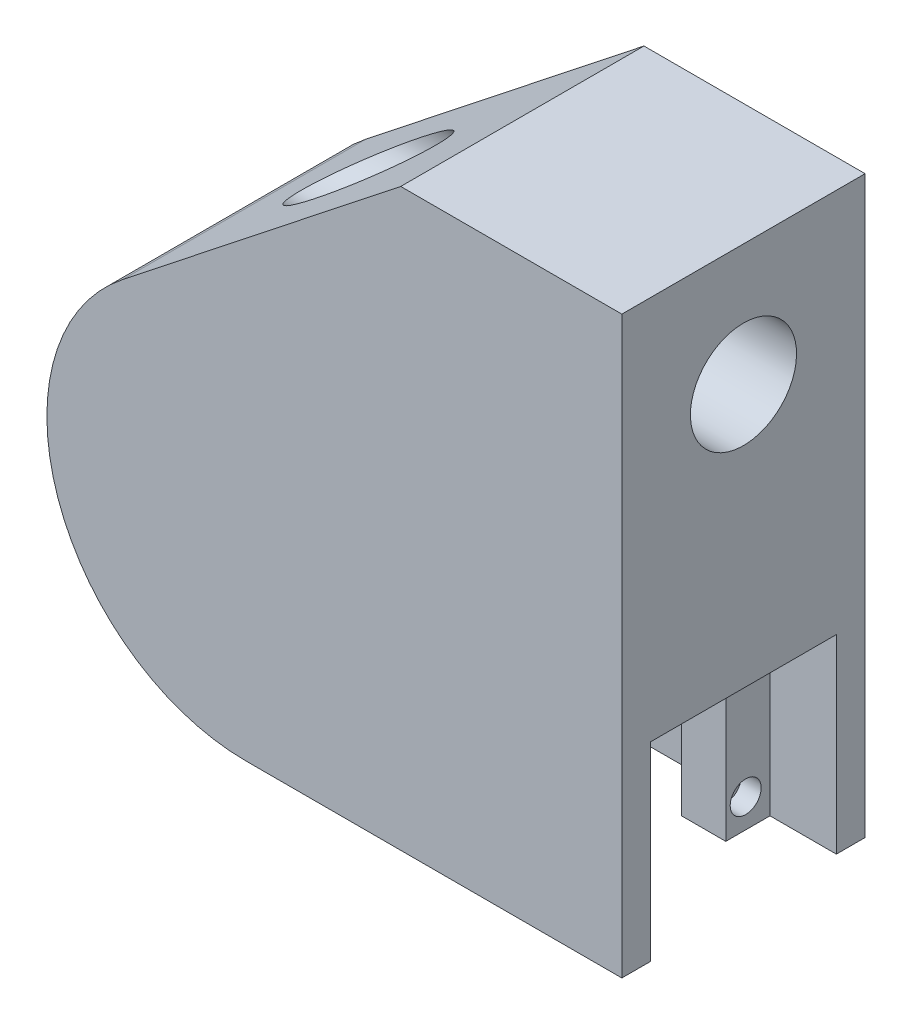
SolidWorks part; units mm, degrees
ref_plane "Ebene vorne" through (0, 0, 0) normal (0, 0, 1) x (1, 0, 0)
ref_plane "Ebene oben" through (0, 0, 0) normal (0, 1, 0) x (1, 0, 0)
ref_plane "Ebene rechts" through (0, 0, 0) normal (1, 0, 0) x (0, 0, -1)
sketch "Skizze1" plane through (0, 0, 0) normal (0, 0, 1) x (1, 0, 0)
  line L0 (35, 85) -> (-27.8961, 35.3102)
  line L1 (85, 85) -> (35, 85)
  line L2 (85, 85) -> (85, 35)
  line L3 (85, 35) -> (35, 35)
  line L4 (35, 85) -> (35, 35)
  line L5 (85, 85) -> (35, 35) construction
  line L6 (85, 35) -> (35, 85) construction
  line L7 (85, 35) -> (85, -45)
  line L8 (85, -45) -> (0, -45)
  circle A0 centre (0, 0) radius 45
  point P3 (60, 60)
  point P9 (0, 0)
  point P12 (-28.951, 34.4505)
  dimension "D1" = 90
  dimension "D2" = 50
  dimension "D3" = 50
  dimension "D4" = 60
  dimension "D5" = 60
extrude "Aufsatz-Linear austragen2" add sketch "Skizze1" along normal blind 55 contours A0 L8 L7 L3 L4 L0 | L1 L4 L3 L2 | A0
sketch "Skizze3" plane through (0, -45, 0) normal (0, -1, 0) x (1, 0, 0)
  line L0 (19, 55) -> (19, 0)
  line L1 (70, 55) -> (19, 55)
  line L2 (70, 55) -> (70, 48.5)
  line L3 (70, 48.5) -> (19, 48.5)
  line L4 (19, 55) -> (19, 48.5)
  line L5 (70, 55) -> (19, 48.5) construction
  line L6 (70, 48.5) -> (19, 55) construction
  line L7 (85, 48.5) -> (85, 6.5)
  line L8 (70, 48.5) -> (60, 48.5)
  line L9 (70, 48.5) -> (70, 38.5)
  line L10 (70, 38.5) -> (60, 38.5)
  line L11 (60, 48.5) -> (60, 38.5)
  line L12 (70, 48.5) -> (60, 38.5) construction
  line L13 (70, 38.5) -> (60, 48.5) construction
  line L14 (70, 0) -> (19, 0)
  line L15 (70, 0) -> (70, 6.5)
  line L16 (70, 6.5) -> (19, 6.5)
  line L17 (19, 0) -> (19, 6.5)
  line L18 (70, 0) -> (19, 6.5) construction
  line L19 (70, 6.5) -> (19, 0) construction
  line L20 (70, 6.5) -> (60, 6.5)
  line L21 (70, 6.5) -> (70, 16.5)
  line L22 (70, 16.5) -> (60, 16.5)
  line L23 (60, 6.5) -> (60, 16.5)
  line L24 (70, 6.5) -> (60, 16.5) construction
  line L25 (70, 16.5) -> (60, 6.5) construction
  line L26 (85, 55) -> (85, 0) construction
  line L28 (70, 55) -> (85, 55)
  line L29 (70, 55) -> (70, 48.5)
  line L30 (70, 48.5) -> (85, 48.5)
  line L31 (85, 55) -> (85, 48.5)
  line L32 (70, 55) -> (85, 48.5) construction
  line L33 (70, 48.5) -> (85, 55) construction
  line L34 (70, 0) -> (85, 0)
  line L35 (70, 0) -> (70, 6.5)
  line L36 (70, 6.5) -> (85, 6.5)
  line L37 (85, 0) -> (85, 6.5)
  line L38 (70, 0) -> (85, 6.5) construction
  line L39 (70, 6.5) -> (85, 0) construction
  point P4 (44.5, 51.75)
  point P11 (65, 43.5)
  point P16 (44.5, 3.25)
  point P21 (65, 11.5)
  point P25 (77.5, 51.75)
  point P27 (77.5, 3.25)
  point P28 (0, 0)
  line M7 (85, 0) -> (85, 55)
  dimension "D1" = 42
  dimension "D2" = 6.5
  dimension "D3" = 22
  dimension "D4" = 10
  dimension "D5" = 10
  dimension "D6" = 41
  dimension "D7" = 15
extrude "Schnitt-Linear austragen1" cut sketch "Skizze3" against normal blind 43 contours L16 L23 L22 L10 L11 L3 L0 M7
sketch "Skizze4" plane through (70, 0, 0) normal (1, 0, 0) x (0, 0, -1)
  line L0 (-38.5, -2) -> (-48.5, -2) construction
  line L3 (-48.5, -2) -> (-6.5, -2)
  line L4 (-48.5, -2) -> (-48.5, -44)
  line L5 (-48.5, -44) -> (-6.5, -44)
  line L6 (-6.5, -2) -> (-6.5, -44)
  line L7 (-48.5, -2) -> (-44.0604, -6.4396) construction
  line L8 (-48.5, -44) -> (-6.5, -2) construction
  line L9 (-55, -45) -> (-48.5, -45) construction
  line L10 (-41.9391, -8.5609) -> (-6.5, -44) construction
  arc A0 (-44.0235, -8.5965) -> (-13.0965, -39.5235) centre (-27.5, -23) ccw
  circle A1 centre (-12.0002, -7.5002) radius 1.5
  circle A2 centre (-12.0002, -38.4998) radius 1.5
  circle A3 centre (-42.9998, -38.4998) radius 1.5
  circle A4 centre (-42.9998, -7.5002) radius 1.5
  arc A5 (-13.0965, -6.4765) -> (-41.9035, -6.4765) centre (-27.5, -23) ccw
  arc A6 (-10.9765, -37.4035) -> (-10.9765, -8.5965) centre (-27.5, -23) ccw
  point P8 (-27.5, -23)
  point P23 (-27.5, -23)
  dimension "D4" = 4
  dimension "D5" = 3
  dimension "D1" = 1
  dimension "D2" = 27.5
  dimension "D3" = 42
extrude "Schnitt-Linear austragen2" cut sketch "Skizze4" against normal blind 10 contours A4 | A1 | A2 | A0 A3 | A0 A3
sketch "Skizze5" plane through (70, 0, 0) normal (1, 0, 0) x (0, 0, -1)
  circle A0 centre (-42.9998, -7.5002) radius 3.5
  circle A1 centre (-12.0002, -7.5002) radius 3.5
  circle A2 centre (-12.0002, -38.4998) radius 3.5
  circle A3 centre (-42.9998, -38.4998) radius 3.5
  dimension "D1" = 7
extrude "Schnitt-Linear austragen3" cut sketch "Skizze5" against normal blind 4.5
ref_plane "Ebene1" through (0, 0, 27.5) normal (0, 0, 1) x (1, 0, 0)
sketch "Skizze6" plane through (0, 0, 27.5) normal (0, 0, 1) x (1, 0, 0)
  line L0 (19, 10.5) -> (5.8095, 10.5)
  line L1 (85, -45) -> (60, -45)
  line L2 (85, -45) -> (85, -2)
  line L3 (85, -2) -> (60, -2)
  line L4 (60, -45) -> (60, -2)
  line L5 (85, -45) -> (60, -2) construction
  line L6 (85, -2) -> (60, -45) construction
  line L7 (60, -45) -> (19, -45)
  line L8 (60, -45) -> (60, -2)
  line L9 (60, -2) -> (19, -2)
  line L10 (19, -45) -> (19, -2)
  line L11 (60, -45) -> (19, -2) construction
  line L12 (60, -2) -> (19, -45) construction
  line L13 (19, -2) -> (29, -2)
  line L14 (19, -2) -> (19, 10.5)
  line L15 (19, 10.5) -> (29, 10.5)
  line L16 (29, -2) -> (29, 10.5)
  line L17 (19, -2) -> (29, 10.5) construction
  line L18 (19, 10.5) -> (29, -2) construction
  line L19 (19, 3) -> (11.619, 3)
  circle A1 centre (0, 0) radius 12
  point P7 (72.5, -23.5)
  point P11 (39.5, -23.5)
  point P15 (24, 4.25)
  point P19 (8.9443, 8)
  point P20 (11.619, 3)
  dimension "D1" = 43
  dimension "D6" = 7.5
  dimension "D7" = 24
  dimension "D2" = 25
  dimension "D3" = 41
  dimension "D4" = 10
  dimension "D5" = 12.5
extrude "Schnitt-Linear austragen4" cut sketch "Skizze6" along normal mid plane 42
sketch "Skizze7" plane through (0, 0, 55) normal (0, 0, 1) x (1, 0, 0)
  circle A0 centre (0, 0) radius 13
  dimension "D1" = 26
extrude "Schnitt-Linear austragen5" cut sketch "Skizze7" against normal blind 49 from offset 6 offset against normal yes
sketch "Skizze8" plane through (85, 0, 0) normal (1, 0, 0) x (0, 0, -1)
  line L0 (-55, 85) -> (-55, -45) construction
  line L1 (-55, 85) -> (0, 85) construction
  line L2 (0, 85) -> (0, -45) construction
  circle A0 centre (-27.5, 57.5) radius 27.5
  circle A1 centre (-27.5, 57.5) radius 12
  point P3 (-23.7907, 53.7712)
extrude "Schnitt-Linear austragen6" cut sketch "Skizze8" against normal through all contours A1
sketch "Skizze9" plane through (0, 0, 0) normal (0, 0, -1) x (-1, 0, 0)
  line L0 (0, 0) -> (-10.0376, 14.3352) construction
  circle A5 centre (0, 0) radius 17.5
  circle A6 centre (-10.0376, 14.3352) radius 1.65
  circle A7 centre (14.3352, 10.0376) radius 1.65
  circle A8 centre (10.0376, -14.3352) radius 1.65
  circle A9 centre (-14.3352, -10.0376) radius 1.65
  point P13 (0, 0)
  dimension "D1" = 35
extrude "Schnitt-Linear austragen9" cut sketch "Skizze9" against normal blind 20 contours A5 A6 | A6 L0 A5 | L0 A6 A5 | A5 A7 | A5 A7 | A5 A9 | A5 A9 | A5 A8 | A5 A8
